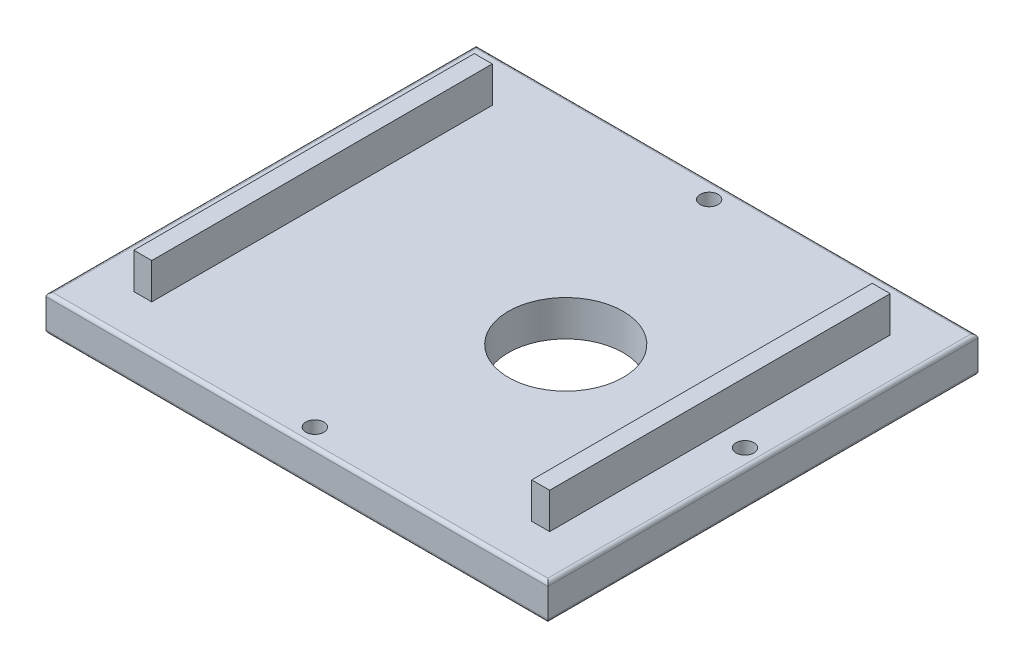
SolidWorks part; units mm, degrees
ref_plane "前视基准面" through (0, 0, 0) normal (0, 0, 1) x (1, 0, 0)
ref_plane "上视基准面" through (0, 0, 0) normal (0, 1, 0) x (1, 0, 0)
ref_plane "右视基准面" through (0, 0, 0) normal (1, 0, 0) x (0, 0, -1)
other "Configuration Table"
sketch "Sketch1" plane through (0, 0, 0) normal (0, 1, 0) x (1, 0, 0)
  line L1 (-70, -60) -> (70, -60)
  line L2 (-70, -60) -> (-70, 60)
  line L3 (-70, 60) -> (70, 60)
  line L4 (70, -60) -> (70, 60)
  point P4 (-70, 0)
  point P6 (0, 60)
  dimension "D1" = 140
  dimension "D2" = 120
extrude "LID_EXTRUDE" add sketch "Sketch1" along normal blind 10
sketch "Sketch3" plane through (0, 10, 0) normal (0, 1, 0) x (1, 0, 0)
  line L0 (0, 20.1916) -> (0, -18.3931) construction
  line L1 (-58, 47.5) -> (-53, 47.5)
  line L2 (-58, 47.5) -> (-58, -47.5)
  line L3 (-58, -47.5) -> (-53, -47.5)
  line L4 (-53, 47.5) -> (-53, -47.5)
  line L5 (58, -47.5) -> (53, -47.5)
  line L6 (53, 47.5) -> (53, -47.5)
  line L7 (58, 47.5) -> (53, 47.5)
  line L8 (58, 47.5) -> (58, -47.5)
  point P7 (-53, 0)
  point P8 (-58, 0)
  dimension "D1" = 58
  dimension "D2" = 95
  dimension "D3" = 5
extrude "LOCATION_BAR_EXTRUDE" add sketch "Sketch3" along normal blind 10
sketch "BOLE_HOLE_CUT" plane through (0, 0, 0) normal (0, -1, 0) x (1, 0, 0)
  point P0 (0, 55)
  point P1 (-65, 0)
  dimension "D1" = 55
  dimension "D2" = 65
hole_wizard "M6 Tapped Hole1" positions "3DSketch1" profile "Sketch5" tap size "M6" standard "ISO" end condition up to next
sketch3d "3DSketch1"
  point P0 (0, 0, 55)
  point P3 (-65, 0, 0)
sketch "Sketch5" plane through (0, 0, 55) normal (1, 0, 0) x (0, 0, -1)
  line L0 (0, 0) -> (0, 10)
  line L1 (0, 10) -> (2.5, 10)
  line L2 (2.5, 10) -> (2.5, 0.525)
  line L3 (2.5, 0.525) -> (3.025, 0)
  line L5 (3.025, 0) -> (0, 0)
  line L6 (-2.5, 0.525) -> (-3.025, 0) construction
  line L11 (0, -6.35) -> (0, 107.95) construction
  dimension "Thru Tap Drill Dia." = 5
  dimension "Thru Tap Drill Depth" = 10
  dimension "Near C'Sink Dia." = 6.05
  dimension "Near C'Sink Angle" = 90
cosmetic thread "Hole Thread1" parameters "D2"=6
cosmetic thread "Hole Thread2" parameters "D2"=6
mirror "Mirror1" about plane through (0, 0, 0) normal (1, 0, 0) of "M6 Tapped Hole1" second plane through (0, 0, 0) second plane normal (0, 0, 1)
sketch "Sketch6" plane through (0, 0, 0) normal (0, -1, 0) x (1, 0, 0)
  circle A0 centre (15, 0) radius 16
  dimension "D2" = 32
  dimension "D1" = 15
extrude "MOTOR_HOLE_CUT" cut sketch "Sketch6" against normal up to next
fillet "Fillet2" radius 1 8 edges at (-70, 10, 0) (0, 10, 60) (0, 10, -60) (70, 10, 0) (70, 0, 0) (0, 0, 60) (-70, 0, 0) (0, 0, -60)
